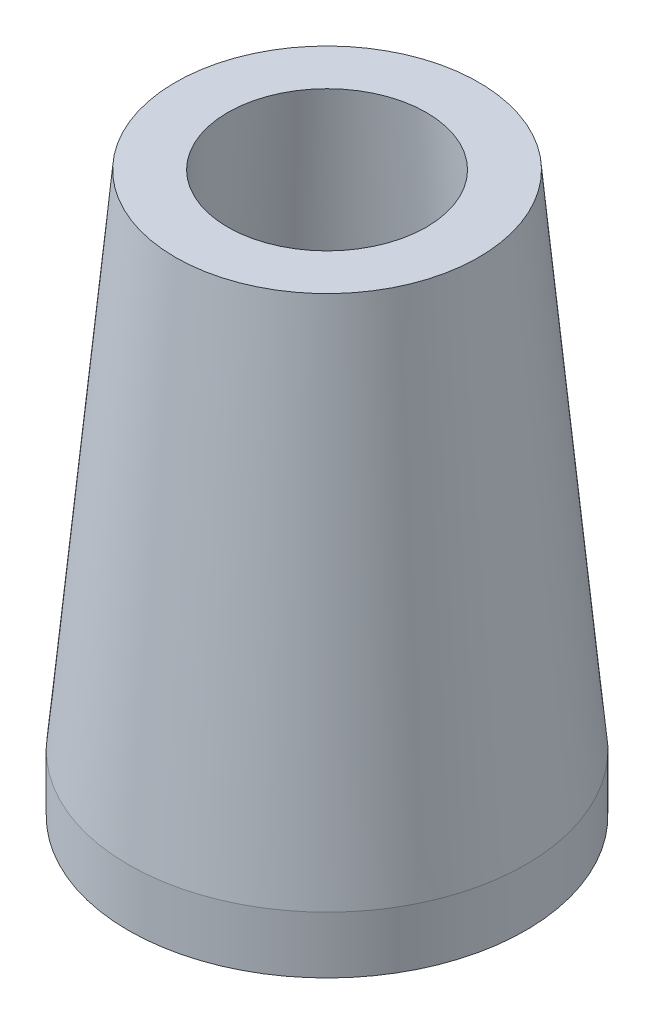
SolidWorks part; units mm, degrees
ref_plane "Front Plane" through (0, 0, 0) normal (0, 0, 1) x (1, 0, 0)
ref_plane "Top Plane" through (0, 0, 0) normal (0, 1, 0) x (1, 0, 0)
ref_plane "Right Plane" through (0, 0, 0) normal (1, 0, 0) x (0, 0, -1)
sketch "Sketch1" plane through (0, 0, 0) normal (0, 0, 1) x (1, 0, 0)
  line L0 (127, 271.5) -> (635, 271.5) construction
  line L1 (434.0182, 194.9999) -> (444.0182, 194.9999)
  line L2 (509.9999, 194.9999) -> (501.0003, 301.998)
  line L3 (452.9992, 301.9988) -> (442.9992, 301.9988)
  line L4 (442.9992, 301.9988) -> (434.0182, 205.8959)
  line L5 (452.9992, 301.9988) -> (445.8146, 204.9999)
  line L6 (419.2726, 0) -> (419.2726, 194.9999)
  line L7 (442.9992, 301.9988) -> (452.9992, 301.9986) construction
  line L8 (501.0003, 301.998) -> (471.9998, 301.9984) construction
  line L9 (471.9998, 301.9984) -> (471.9998, 194.9999) construction
  line L10 (434.0182, 194.9999) -> (434.0182, 205.8959)
  line L11 (444.0182, 204.9999) -> (445.8146, 204.9999) construction
  line L12 (444.0182, 194.9999) -> (444.0182, 204.9999)
  line L13 (445.8146, 204.9999) -> (444.0182, 204.9999)
  line L14 (471.9998, 301.9984) -> (501.0003, 301.998) construction
  dimension "D1" = 106.9988
ref_plane "Plane2" through (0, 195, 0) normal (0, 1, 0) x (1, 0, 0)
sketch "Sketch3" plane through (0, 195, 0) normal (0, 1, 0) x (1, 0, 0)
  line L0 (434.0182, 0) -> (444.0182, 0) construction
  circle A0 centre (471.5, 0) radius 38
sketch "Sketch4" plane through (0, 0, 0) normal (0, 0, 1) x (1, 0, 0)
ref_plane "Plane3" through (0, 302, 0) normal (0, 1, 0) x (1, 0, 0)
revolve "Revolve2" add sketch "Sketch1" angle 360 about L9
